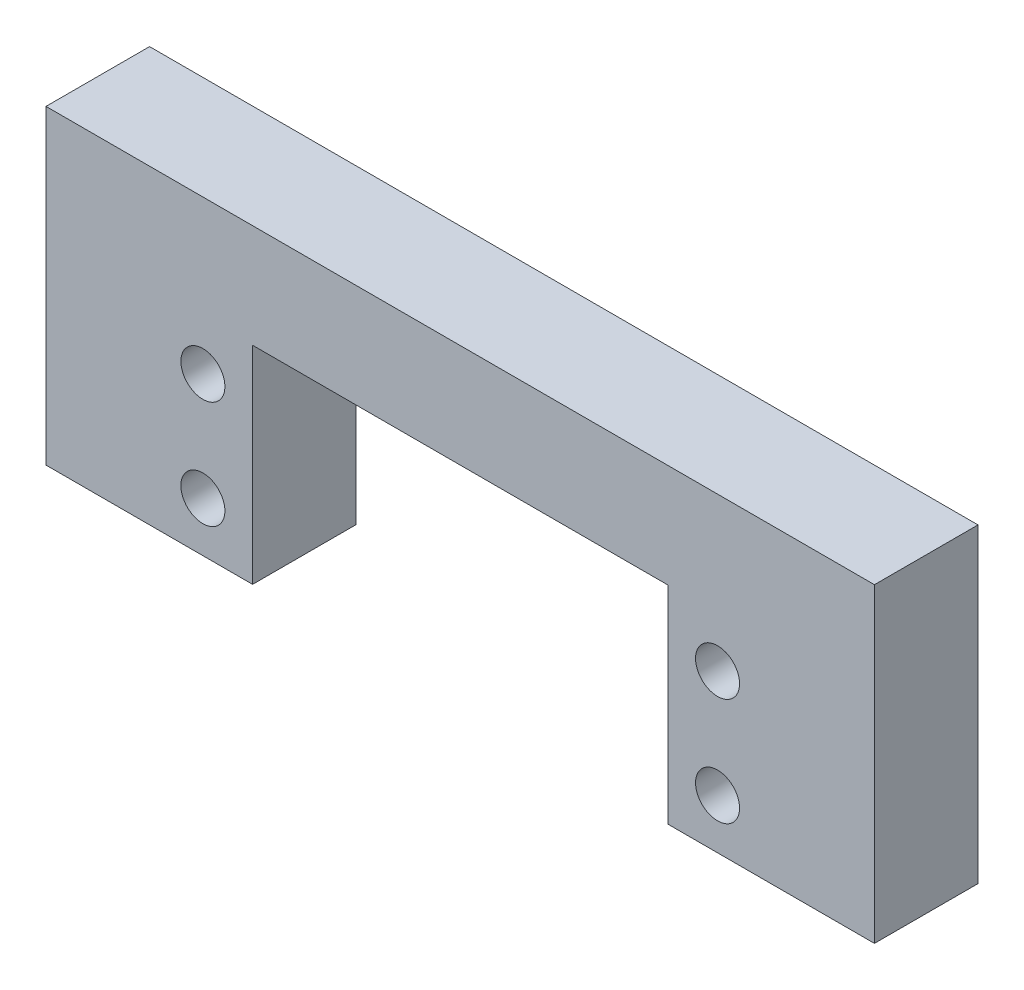
SolidWorks part; units mm, degrees
ref_plane "Front" through (0, 0, 0) normal (0, 0, 1) x (1, 0, 0)
ref_plane "Top" through (0, 0, 0) normal (0, 1, 0) x (1, 0, 0)
ref_plane "Right" through (0, 0, 0) normal (1, 0, 0) x (0, 0, -1)
sketch "Sketch1" plane through (0, 0, 0) normal (0, 0, 1) x (1, 0, 0)
  line L1 (0, 0) -> (19.95, 0)
  line L2 (0, 0) -> (0, 30)
  line L3 (0, 30) -> (80, 30)
  line L4 (80, 0) -> (80, 30)
  line L6 (19.95, 0) -> (19.95, 20)
  line L7 (19.95, 20) -> (60.05, 20)
  line L8 (60.05, 0) -> (60.05, 20)
  line L10 (60.05, 0) -> (80, 0)
  dimension "D1" = 80
  dimension "D2" = 30
  dimension "D4" = 19.95
  dimension "D3" = 10
  dimension "D5" = 19.95
  dimension "D6" = 40.1
extrude "Boss-Extrude1" add sketch "Sketch1" along normal blind 10
sketch "Sketch2" plane through (0, 0, 0) normal (0, -1, 0) x (1, 0, 0)
  circle A0 centre (5, 5) radius 2
  circle A1 centre (75, 5) radius 2
  dimension "D1" = 70
extrude "Cut-Extrude1" cut sketch "Sketch2" against normal blind 15
sketch "Sketch3" plane through (0, 0, 10) normal (0, 0, 1) x (1, 0, 0)
  line L0 (0, 0) -> (19.95, 0) construction
  line L1 (19.95, 0) -> (19.95, 20) construction
  line L2 (40, 17.0188) -> (40, 23.436) construction
  line L8 (60.05, 20) -> (60.05, 0) construction
  circle A0 centre (15.15, 4.8) radius 2.125
  circle A1 centre (15.15, 15.2) radius 2.125
  circle A2 centre (64.85, 15.2) radius 2.125
  circle A3 centre (64.85, 4.8) radius 2.125
  dimension "D1" = 4.8
  dimension "D3" = 10.4
  dimension "D2" = 4.8
  dimension "D4" = 4.8
  dimension "D5" = 49.7
extrude "Cut-Extrude2" cut sketch "Sketch3" against normal through all
